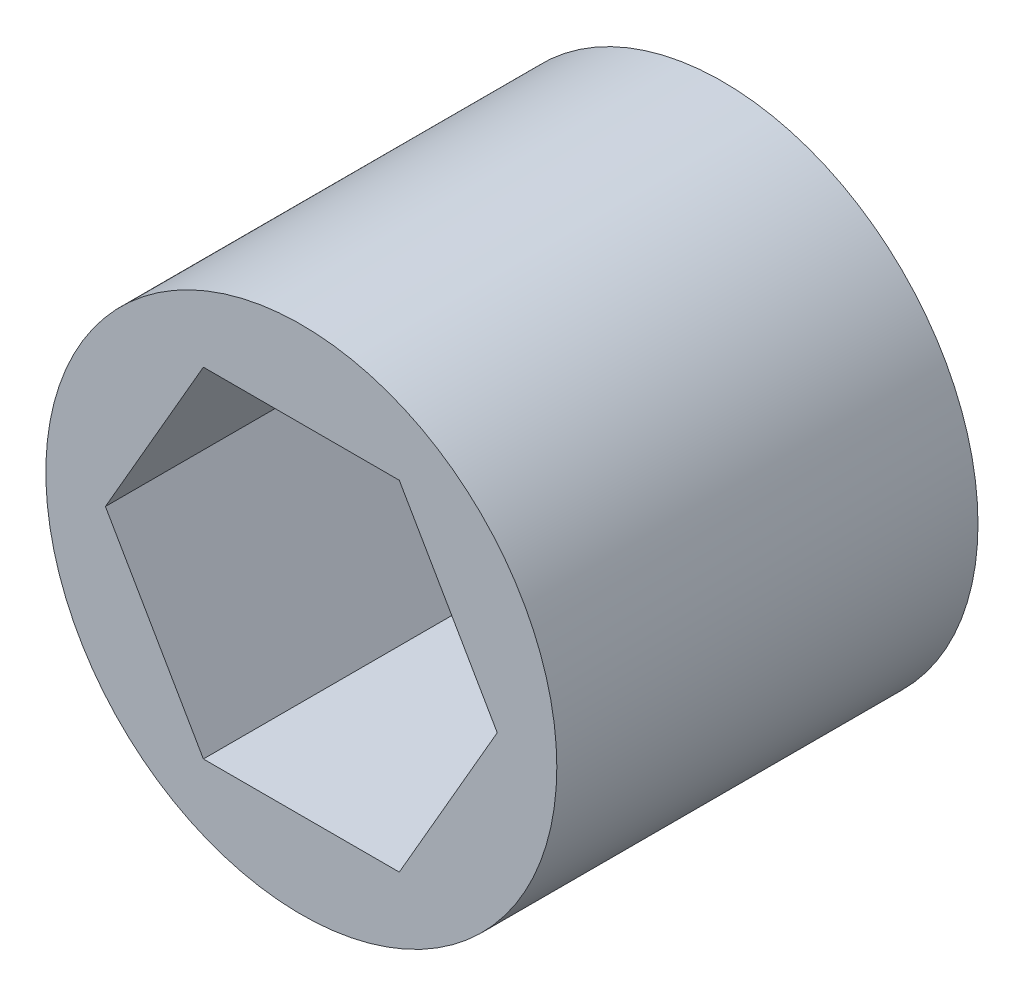
SolidWorks part; units mm, degrees
ref_plane "Front Plane" through (0, 0, 0) normal (0, 0, 1) x (1, 0, 0)
ref_plane "Top Plane" through (0, 0, 0) normal (0, 1, 0) x (1, 0, 0)
ref_plane "Right Plane" through (0, 0, 0) normal (1, 0, 0) x (0, 0, -1)
sketch "Sketch2" plane through (0, 0, 0) normal (0, 0, 1) x (1, 0, 0)
  line L1 (7.479, 0) -> (3.7395, 6.477)
  line L2 (3.7395, 6.477) -> (-3.7395, 6.477)
  line L3 (-3.7395, 6.477) -> (-7.479, 0)
  line L4 (-7.479, 0) -> (-3.7395, -6.477)
  line L5 (-3.7395, -6.477) -> (3.7395, -6.477)
  line L6 (3.7395, -6.477) -> (7.479, 0)
  circle A0 centre (0, 0) radius 6.477 construction
  circle A1 centre (0, 0) radius 9.7536
  dimension "D1" = 19.5072
  dimension "D2" = 12.954
extrude "Boss-Extrude2" add sketch "Sketch2" along normal blind 16.0782
